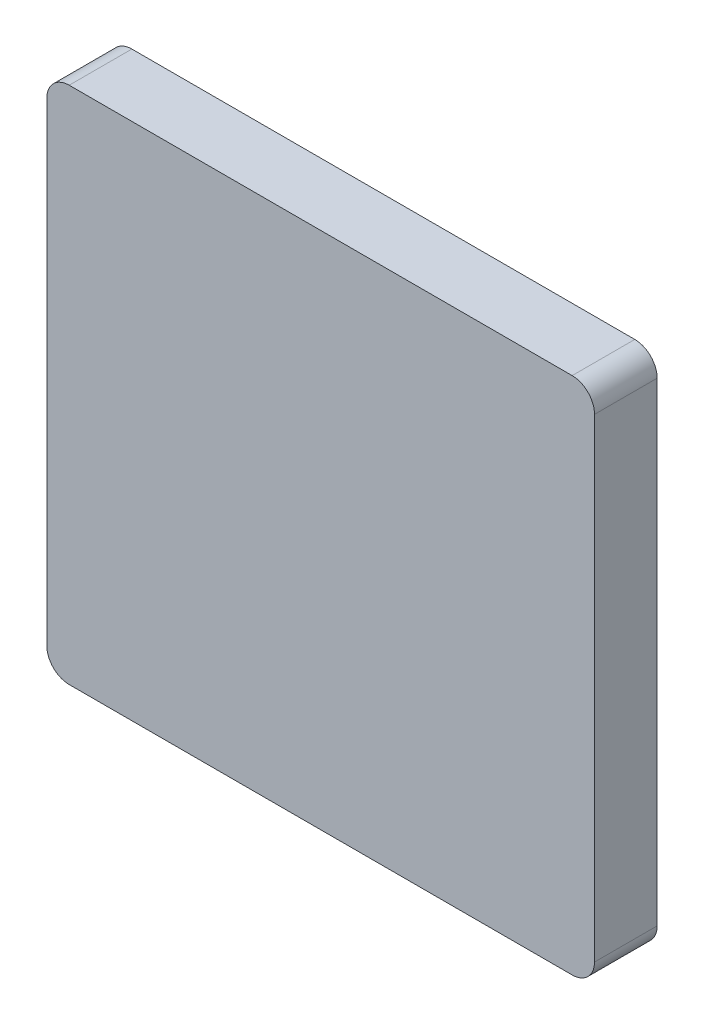
SolidWorks part; units mm, degrees
material "Alloy Steel (SS)"
ref_plane "Front Plane" through (0, 0, 0) normal (0, 0, 1) x (1, 0, 0)
ref_plane "Top Plane" through (0, 0, 0) normal (0, 1, 0) x (1, 0, 0)
ref_plane "Right Plane" through (0, 0, 0) normal (1, 0, 0) x (0, 0, -1)
sketch "Sketch1" plane through (0, 0, 0) normal (0, 0, 1) x (1, 0, 0)
  line L1 (-446.1538, -290) -> (165.8462, -290)
  line L2 (-446.1538, -290) -> (-446.1538, 290)
  line L3 (-446.1538, 290) -> (165.8462, 290)
  line L4 (165.8462, -290) -> (165.8462, 290)
  line L5 (-446.1538, -290) -> (165.8462, 290) construction
  line L6 (-446.1538, 290) -> (165.8462, -290) construction
  point P0 (0, 0)
  dimension "D1" = 580
  dimension "D2" = 612
extrude "Boss-Extrude1" add sketch "Sketch1" along normal blind 70
fillet "Fillet1" radius 25 4 edges at (165.8462, 290, 35) (-446.1538, 290, 35) (-446.1538, -290, 35) (165.8462, -290, 35)
